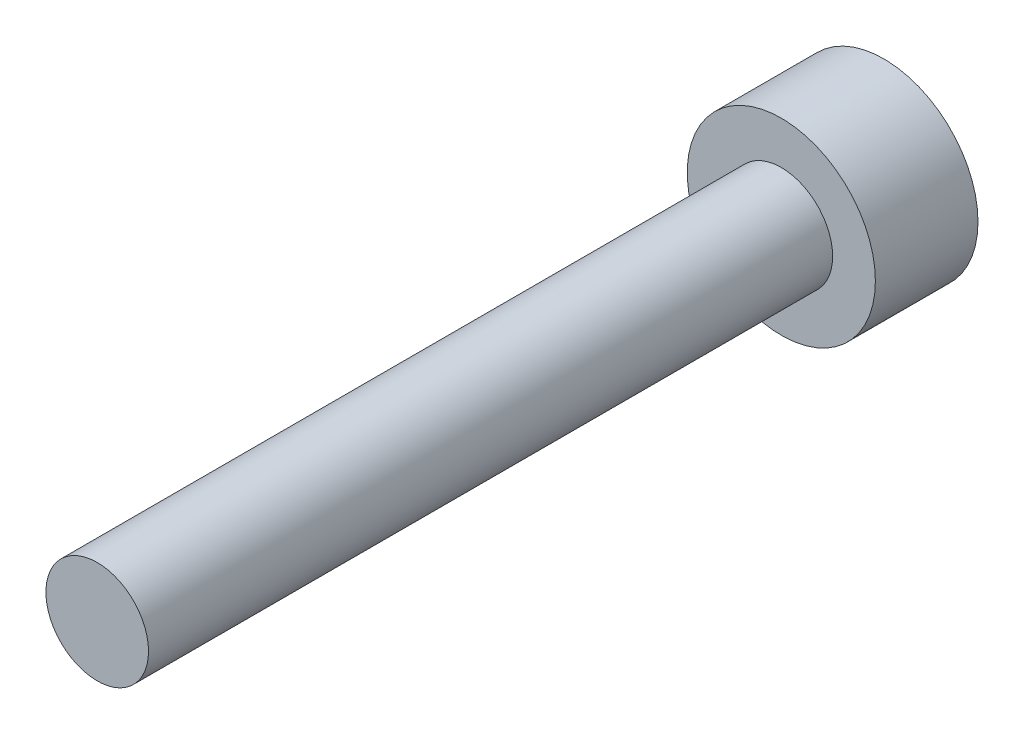
SolidWorks part; units mm, degrees
ref_plane "前视基准面" through (0, 0, 0) normal (0, 0, 1) x (1, 0, 0)
ref_plane "上视基准面" through (0, 0, 0) normal (0, 1, 0) x (1, 0, 0)
ref_plane "右视基准面" through (0, 0, 0) normal (1, 0, 0) x (0, 0, -1)
other "Configuration Table"
sketch "草图1" plane through (0, 0, 0) normal (0, 0, 1) x (1, 0, 0)
  circle A0 centre (0, 0) radius 2.75
  dimension "D1" = 5.5
extrude "凸台-拉伸1" add sketch "草图1" along normal blind 3
sketch "草图2" plane through (0, 0, 3) normal (0, 0, 1) x (1, 0, 0)
  circle A0 centre (0, 0) radius 1.5
  dimension "D1" = 3
extrude "凸台-拉伸2" add sketch "草图2" along normal blind 20
